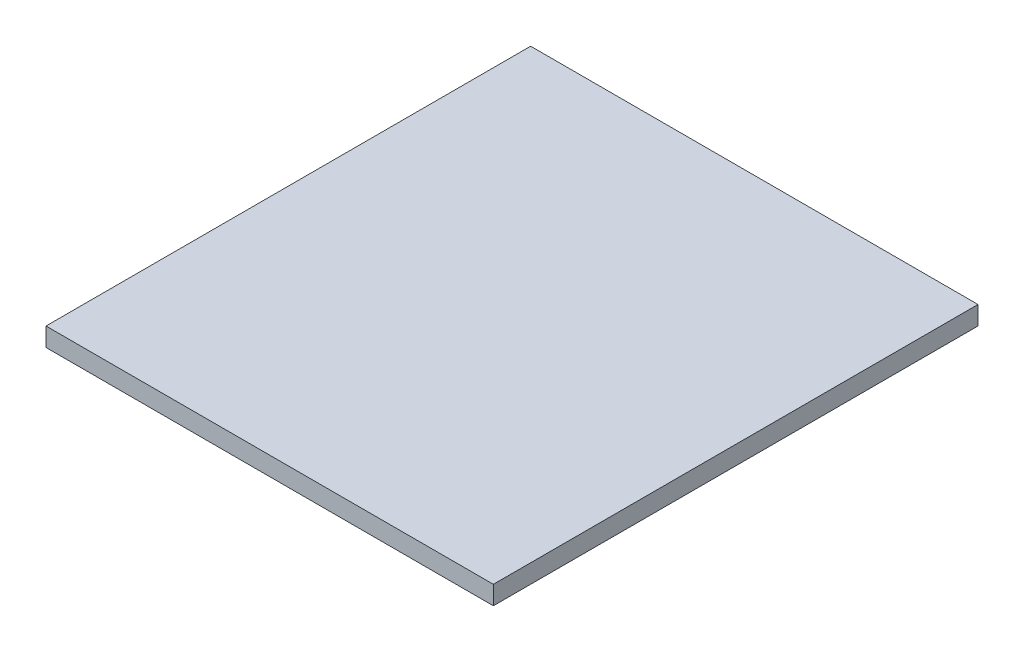
SolidWorks part; units mm, degrees
material "Pine"
ref_plane "Front Plane" through (0, 0, 0) normal (0, 0, 1) x (1, 0, 0)
ref_plane "Top Plane" through (0, 0, 0) normal (0, 1, 0) x (1, 0, 0)
ref_plane "Right Plane" through (0, 0, 0) normal (1, 0, 0) x (0, 0, -1)
sketch "Sketch1" plane through (0, 0, 0) normal (0, 1, 0) x (1, 0, 0)
  line L1 (0, 0) -> (304.8, 0)
  line L2 (0, 0) -> (0, 330.2)
  line L3 (0, 330.2) -> (304.8, 330.2)
  line L4 (304.8, 0) -> (304.8, 330.2)
  dimension "D1" = 304.8
  dimension "D2" = 330.2
extrude "Boss-Extrude1" add sketch "Sketch1" along normal blind 12.7
